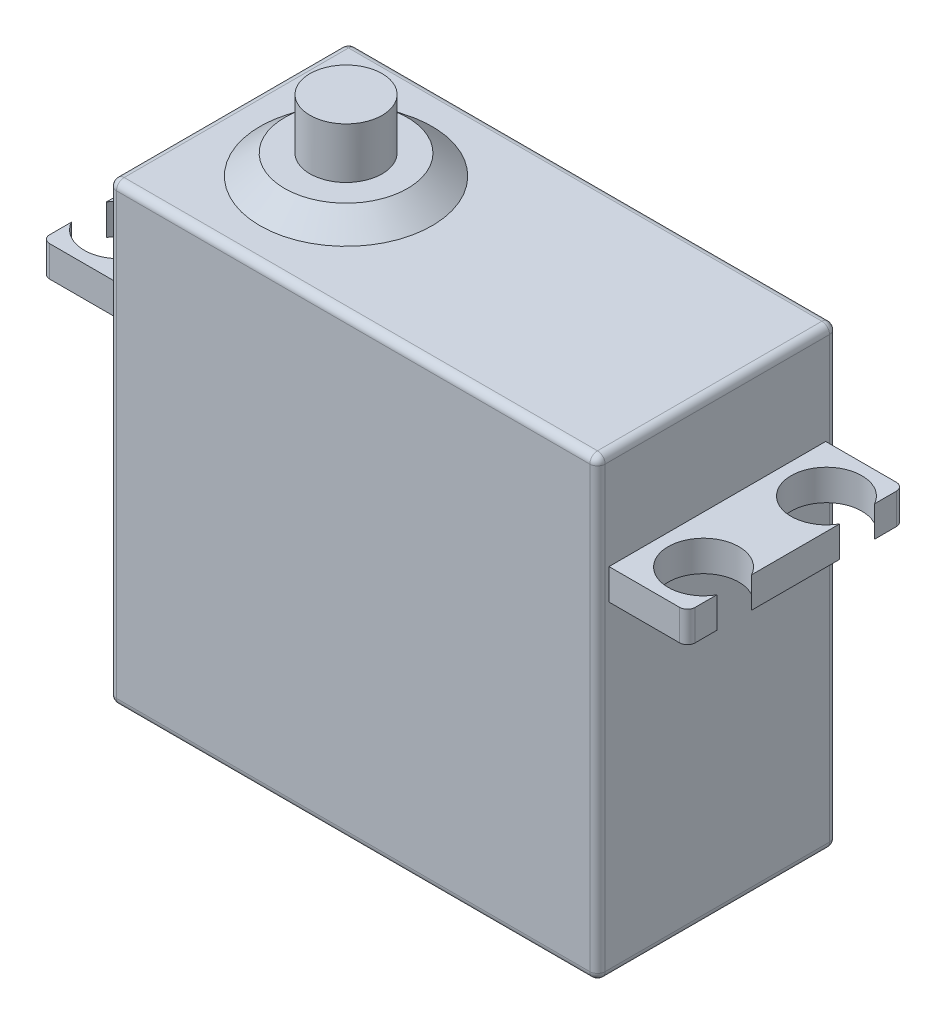
SolidWorks part; units mm, degrees
ref_plane "Front" through (0, 0, 0) normal (0, 0, 1) x (1, 0, 0)
ref_plane "Top" through (0, 0, 0) normal (0, 1, 0) x (1, 0, 0)
ref_plane "Right" through (0, 0, 0) normal (1, 0, 0) x (0, 0, -1)
sketch "body" plane through (0, 0, 0) normal (0, 1, 0) x (1, 0, 0)
  line L0 (-20.193, -9.906) -> (20.193, 9.906) construction
  line L1 (-20.193, 9.906) -> (20.193, 9.906)
  line L2 (-20.193, 9.906) -> (-20.193, -9.906)
  line L3 (-20.193, -9.906) -> (20.193, -9.906)
  line L4 (20.193, 9.906) -> (20.193, -9.906)
  point P4 (20.193, 0)
  point P5 (0, -9.8425)
  dimension "body_length" = 40.386
  dimension "body_width" = 19.812
extrude "servo_body" add sketch "body" along normal blind 37.592
sketch "tab" plane through (-20.193, 0, 0) normal (-1, 0, 0) x (0, 0, 1)
  line L0 (-9.906, 37.592) -> (9.906, 37.592) construction
  line L1 (-8.9535, 29.464) -> (8.9535, 29.464)
  line L2 (-8.9535, 29.464) -> (-8.9535, 26.924)
  line L3 (-8.9535, 26.924) -> (8.9535, 26.924)
  line L4 (8.9535, 29.464) -> (8.9535, 26.924)
  point P4 (0, 26.924)
  dimension "tab_thickness" = 2.54
  dimension "tab_width" = 17.907
  dimension "tab_base_to_body_top" = 10.668
extrude "mounting_tab" add sketch "tab" along normal blind 6.477
fillet "Fillet1" radius 0.635 2 edges at (-26.67, 28.194, -8.9535) (-26.67, 28.194, 8.9535)
sketch "holes" plane through (0, 29.464, 0) normal (0, 1, 0) x (-1, 0, 0)
  line L0 (17.7292, 0) -> (32.999, 0) construction
  line L2 (20.193, -9.906) -> (20.193, 9.906) construction
  circle A0 centre (24.13, -5.08) radius 2.921
  circle A1 centre (24.13, 5.08) radius 2.921
  dimension "mounting_hole_diameter" = 5.842
  dimension "mounting_hole_separation" = 10.16
  dimension "side_to_mounting_hole" = 3.937
extrude "mounting_holes" cut sketch "holes" against normal through all
mirror "mounting_tab_2" about plane through (0, 0, 0) normal (1, 0, 0) of "mounting_holes", "Fillet1", "mounting_tab"
sketch "Sketch4" plane through (0, 0, 0) normal (0, 0, 1) x (1, 0, 0)
  line L0 (-10.4902, 39.5987) -> (-10.4902, 33.7063) construction
  line L1 (-10.4902, 37.592) -> (-3.3782, 37.592)
  line L2 (-3.3782, 37.592) -> (-5.4102, 39.243)
  line L3 (-5.4102, 39.243) -> (-10.4902, 39.243)
  line L4 (-10.4902, 39.243) -> (-10.4902, 37.592)
  line L5 (-20.193, 37.592) -> (20.193, 37.592) construction
  line L6 (-20.193, 37.592) -> (-20.193, 0) construction
  dimension "boss_top_dia" = 10.16
  dimension "boss_bottom_dia" = 14.224
  dimension "boss_height" = 1.651
  dimension "body_edge_to_shaft" = 9.7028
revolve "Boss-Revolve1" add sketch "Sketch4" angle 360 about L0
sketch "shaft" plane through (0, 39.243, 0) normal (0, 1, 0) x (-1, 0, 0)
  line L0 (23.8887, 0) -> (-23.8887, 0) construction
  circle A0 centre (10.4902, 0) radius 2.9845
  circle A1 centre (10.4902, 0) radius 5.08 construction
  dimension "D1" = 5.969
extrude "spline_shaft" add sketch "shaft" along normal blind 4.191
fillet "Fillet2" radius 0.635 12 edges at (20.193, 37.592, 0) (0, 37.592, -9.906) (-20.193, 37.592, 0) (0, 0, -9.906) (20.193, 0, 0) (0, 0, 9.906) (-20.193, 0, 0) (0, 37.592, 9.906) (-20.193, 18.796, -9.906) (20.193, 18.796, -9.906) (20.193, 18.796, 9.906) (-20.193, 18.796, 9.906)
